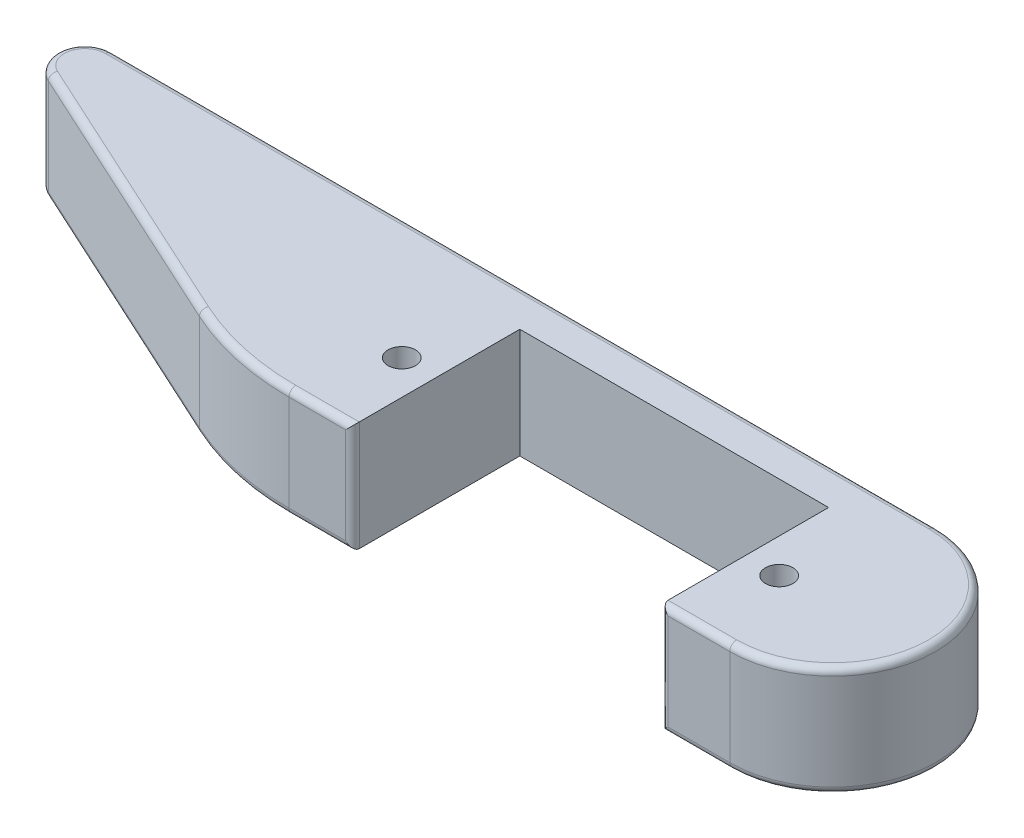
SolidWorks part; units mm, degrees
ref_plane "前基準面" through (0, 0, 0) normal (0, 0, 1) x (1, 0, 0)
ref_plane "上基準面" through (0, 0, 0) normal (0, 1, 0) x (1, 0, 0)
ref_plane "右基準面" through (0, 0, 0) normal (1, 0, 0) x (0, 0, -1)
sketch "草圖1" plane through (0, 0, 0) normal (0, 1, 0) x (1, 0, 0)
  line L0 (0, 0) -> (0, 12.2)
  line L1 (0, 12.2) -> (-22.5, 12.2)
  line L2 (-22.5, 12.2) -> (-22.5, 0)
  line L3 (5, 15) -> (-55, 15)
  line L4 (-55.8351, 11.1827) -> (-35.4752, 1.8269)
  line L5 (-27.1243, 0) -> (-22.5, 0)
  line L6 (5, 0) -> (0, 0)
  line L7 (-22.5, 12.2) -> (0, 0) construction
  line L8 (-25, 6.1) -> (2.5, 6.1) construction
  line L9 (-11.25, 6.1) -> (-22.5, 0) construction
  arc A0 (5, 0) -> (5, 15) centre (5, 7.5) ccw
  arc A1 (-55, 15) -> (-55.8351, 11.1827) centre (-55, 13) ccw
  arc A2 (-35.4752, 1.8269) -> (-27.1243, 0) centre (-27.1243, 20) ccw
  circle A3 centre (-25, 6.1) radius 1
  circle A4 centre (2.5, 6.1) radius 1
  dimension "D3" = 20
  dimension "D4" = 2
  dimension "D6" = 7.5
  dimension "D9" = 2
  dimension "D1" = 22.5
  dimension "D2" = 12.2
  dimension "D5" = 5
  dimension "D7" = 60
  dimension "D8" = 27.5
extrude "填料-伸長1" add sketch "草圖1" along normal blind 8
fillet "圓角3" radius 0.5 16 edges at (2.5, 8, 0) (12.5, 8, -7.5) (-24.8122, 8, 0) (-31.3985, 8, -0.4621) (-45.6552, 8, -6.5048) (-56.9538, 8, -13.4274) (2.5, 0, 0) (12.5, 0, -7.5) (-24.8122, 0, 0) (-31.3985, 0, -0.4621) (-45.6552, 0, -6.5048) (-56.9538, 0, -13.4274) (-25, 8, -15) (-25, 0, -15) (0, 4, 0) (-22.5, 4, 0)
